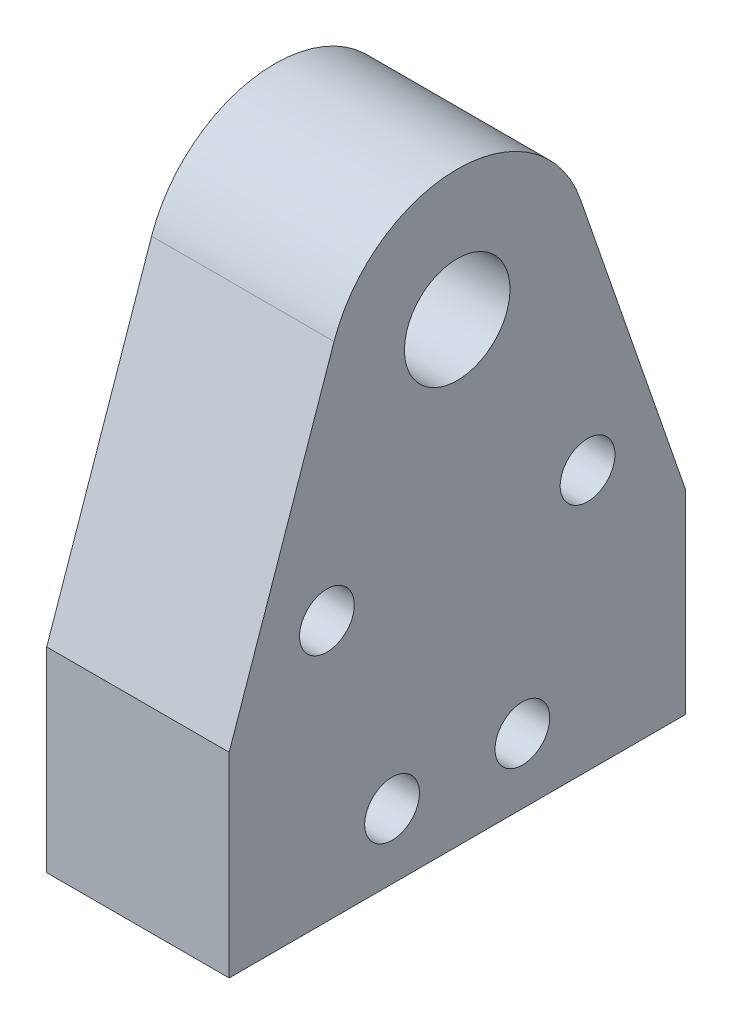
SolidWorks part; units mm, degrees
material "1060 合金"
ref_plane "前视基准面" through (0, 0, 0) normal (0, 0, 1) x (1, 0, 0)
ref_plane "上视基准面" through (0, 0, 0) normal (0, 1, 0) x (1, 0, 0)
ref_plane "右视基准面" through (0, 0, 0) normal (1, 0, 0) x (0, 0, -1)
sketch "草图1" plane through (0, 0, 0) normal (0, 1, 0) x (1, 0, 0)
  line L1 (-7, -17.5) -> (7, -17.5)
  line L2 (-7, -17.5) -> (-7, 17.5)
  line L3 (-7, 17.5) -> (7, 17.5)
  line L4 (7, -17.5) -> (7, 17.5)
  line L5 (-7, -17.5) -> (7, 17.5) construction
  line L6 (-7, 17.5) -> (7, -17.5) construction
  point P0 (0, 0)
  dimension "D1" = 35
  dimension "D2" = 14
extrude "凸台-拉伸1" add sketch "草图1" along normal blind 60
sketch "草图2" plane through (7, 0, 0) normal (1, 0, 0) x (0, 0, -1)
  line L3 (-17.5, 0) -> (-17.5, 60)
  line L4 (-17.5, 60) -> (17.5, 60)
  line L5 (17.5, 60) -> (17.5, 0)
  line L6 (-17.5, 15) -> (-8.9543, 39.7036)
  line L7 (-17.5, 18.4529) -> (-17.5, 0)
  line L8 (-17.5, 0) -> (17.5, 0) construction
  line L9 (17.5, 16.9957) -> (17.5, 0)
  line L10 (-8.9543, 39.7036) -> (-8.4567, 40.3371)
  line L11 (9.4505, 38.2692) -> (17.5, 15)
  circle A0 centre (0, 35) radius 10
  dimension "D1" = 20
  dimension "D3" = 15
  dimension "D4" = 35
  dimension "D10" = 10
  dimension "D11" = 17.5
  dimension "D2" = 0
  dimension "D5" = 0
  dimension "D6" = 0
  dimension "D7" = 0
  dimension "D8" = 15
  dimension "D9" = 10
extrude "切除-拉伸1" cut sketch "草图2" against normal blind 60
sketch "草图3" plane through (0, 0, 0) normal (0, -1, 0) x (1, 0, 0)
  line L0 (0, 12.5) -> (0, -12.5)
  circle A0 centre (0, -12.5) radius 2.1
  circle A1 centre (0, 12.5) radius 2.1
  dimension "D3" = 4.2
  dimension "D4" = 4.2
  dimension "D1" = 25
  dimension "D2" = 12.5
extrude "切除-拉伸2" cut sketch "草图3" against normal blind 10
sketch "草图4" plane through (7, 0, 0) normal (1, 0, 0) x (0, 0, -1)
  circle A0 centre (0, 35) radius 4.05
  dimension "D1" = 8.1
extrude "切除-拉伸3" cut sketch "草图4" against normal blind 46
sketch "草图5" plane through (7, 0, 0) normal (1, 0, 0) x (0, 0, -1)
  line L0 (-17.5, 15) -> (17.5, 15)
  line L1 (0, 15) -> (0, 20)
  line L2 (-10, 20) -> (10, 20)
  line L4 (-10, 20) -> (10, 20)
  line L5 (-10, 20) -> (-10, 5)
  line L6 (-10, 5) -> (10, 5)
  line L7 (10, 20) -> (10, 5)
  circle A0 centre (-10, 20) radius 2.1
  circle A1 centre (10, 20) radius 2.1
  circle A4 centre (-5, 5) radius 2.1
  circle A5 centre (5, 5) radius 2.1
  point P10 (0, 20)
  dimension "D3" = 4.2
  dimension "D4" = 4.2
  dimension "D6" = 10
  dimension "D7" = 5
  dimension "D8" = 4.2
  dimension "D9" = 4.2
  dimension "D1" = 20
  dimension "D2" = 5
  dimension "D5" = 15
extrude "切除-拉伸4" cut sketch "草图5" against normal blind 100 contours L5 A0 L2 | L2 A0 L5 | L4 A1 L7 | L7 A1 L4 | L6 A5 | L6 A5 | L6 A4 | L6 A4
sketch "草图7" plane through (-7, 0, 0) normal (-1, 0, 0) x (0, 0, 1)
  circle A0 centre (0, 35) radius 4.05
extrude "凸台-拉伸3" add sketch "草图7" against normal blind 2 separate body
combine bodies "组合1" operation type add bodies to combine 110 113
